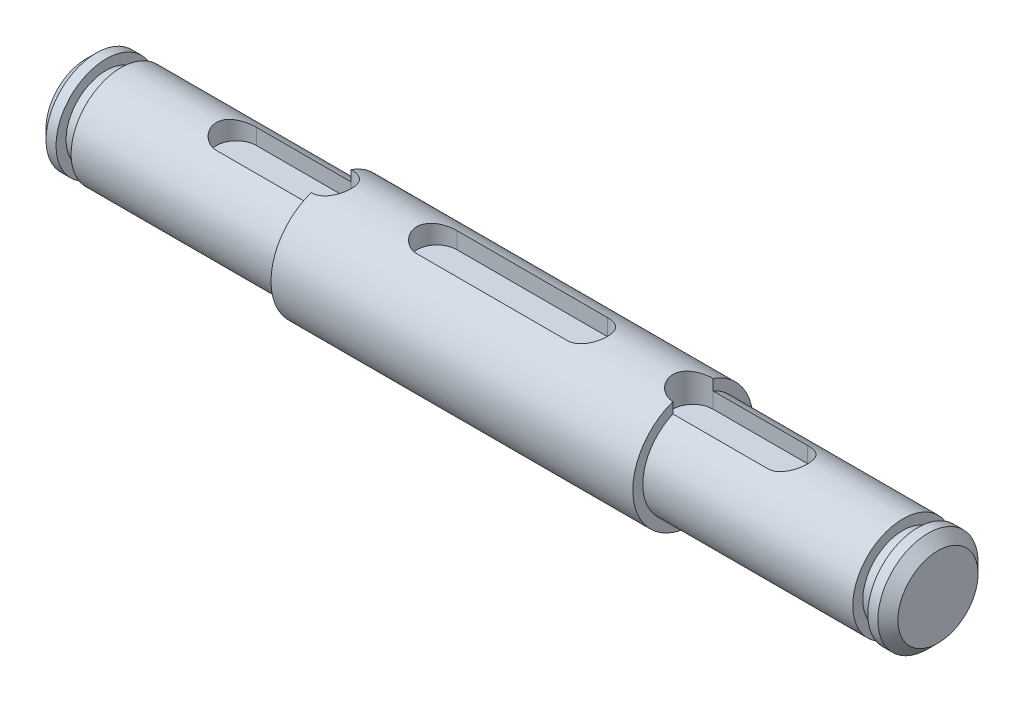
SolidWorks part; units mm, degrees
material "Plain Carbon Steel"
ref_plane "Front Plane" through (0, 0, 0) normal (0, 0, 1) x (1, 0, 0)
ref_plane "Top Plane" through (0, 0, 0) normal (0, 1, 0) x (1, 0, 0)
ref_plane "Right Plane" through (0, 0, 0) normal (1, 0, 0) x (0, 0, -1)
sketch "Sketch1" plane through (0, 0, 0) normal (0, 0, 1) x (1, 0, 0)
  line L0 (-42.5, 0) -> (-42.5, 5)
  line L1 (-42.5, 0) -> (42.5, 0)
  line L2 (-42.5, 5) -> (-40.5, 5)
  line L3 (-40.5, 5) -> (-40.5, 4)
  line L4 (-40.5, 4) -> (-39, 4)
  line L5 (-39, 4) -> (-39, 5)
  line L6 (-39, 5) -> (-18.05, 5)
  line L7 (-47.152, 0) -> (-42.5, 0) construction
  line L8 (0, 5) -> (0, 0) construction
  line L9 (39, 4) -> (39, 5)
  line L10 (40.5, 4) -> (39, 4)
  line L11 (40.5, 5) -> (40.5, 4)
  line L12 (42.5, 5) -> (40.5, 5)
  line L13 (42.5, 0) -> (42.5, 5)
  line L14 (-18.05, 5) -> (-18.05, 6)
  line L15 (-18.05, 6) -> (18.05, 6)
  line L16 (18.05, 6) -> (18.05, 5)
  line L17 (18.05, 5) -> (39, 5)
  dimension "D1" = 10
  dimension "D2" = 78
  dimension "D3" = 1.5
  dimension "D4" = 8
  dimension "D5" = 2
  dimension "D6" = 12
  dimension "D7" = 36.1
revolve "Revolve1" add sketch "Sketch1" angle 360 about L7
chamfer "Chamfer1" distance 1 angle 45 2 edges at (42.5, 0, 5) (-42.5, 0, 5)
sketch "Sketch3" plane through (0, 0, 0) normal (1, 0, 0) x (0, 0, -1)
  line L0 (2, 7) -> (2, 3)
  line L1 (2, 7) -> (-2, 7)
  line L2 (2, 3) -> (-2, 3)
  line L3 (-2, 7) -> (-2, 3)
  line L4 (2, 7) -> (-2, 3) construction
  line L5 (2, 3) -> (-2, 7) construction
  line L6 (0, 5) -> (0, 0) construction
  circle A0 centre (0, 0) radius 5 construction
  point P1 (0, 5)
  dimension "D1" = 4
  dimension "D2" = 4
extrude "Cut-Extrude1" cut sketch "Sketch3" against normal blind 5
sketch "Sketch4" plane through (0, 3, 0) normal (0, 1, 0) x (1, 0, 0)
  line L0 (27.5, 0) -> (-27.5, 0) construction
  line L1 (0, -2) -> (0, 2) construction
  line L2 (27.5, -2) -> (18.05, -2)
  line L3 (27.5, 2) -> (18.05, 2)
  line L4 (-5, 2) -> (0, 2) construction
  line L5 (-18.05, 6) -> (-18.05, -6) construction
  line L6 (-18.05, 5) -> (-18.05, -5) construction
  line L7 (0, 0) -> (0, -8.0271) construction
  line L8 (-18.05, 2) -> (-27.5, 2)
  line L9 (-18.05, -2) -> (-27.5, -2)
  line L10 (-5, -2) -> (0, -2) construction
  arc A0 (27.5, -2) -> (27.5, 2) centre (27.5, 0) ccw
  arc A1 (-27.5, 2) -> (-27.5, -2) centre (-27.5, 0) ccw
  arc A2 (-18.05, 2) -> (-18.05, -2) centre (-18.05, 0) cw
  arc A3 (18.05, 2) -> (18.05, -2) centre (18.05, 0) ccw
  point P4 (0, 0)
  dimension "D1" = 55
extrude "Cut-Extrude2" cut sketch "Sketch4" along normal blind 10
sketch "Sketch5" plane through (0, 3, 0) normal (0, 1, 0) x (1, 0, 0)
  line L0 (7.5, 0) -> (-7.5, 0) construction
  line L1 (0, -2) -> (0, 2) construction
  line L2 (7.5, -2) -> (-7.5, -2)
  line L3 (7.5, 2) -> (-7.5, 2)
  arc A0 (7.5, -2) -> (7.5, 2) centre (7.5, 0) ccw
  arc A1 (-7.5, 2) -> (-7.5, -2) centre (-7.5, 0) ccw
  arc A2 (-18.05, -2) -> (-18.05, 2) centre (-18.05, 0) ccw construction
  point P4 (0, 0)
  dimension "D1" = 15
extrude "Cut-Extrude3" cut sketch "Sketch5" along normal blind 10 from offset 1
sketch "Sketch6" plane through (0, 4, 0) normal (0, 1, 0) x (1, 0, 0)
  line L0 (-5, 2) -> (0, 2)
  line L1 (-5, 2) -> (-5, -2)
  line L2 (0, 2) -> (0, -2)
  line L3 (-5, -2) -> (0, -2)
extrude "Boss-Extrude1" add sketch "Sketch6" against normal up to next
